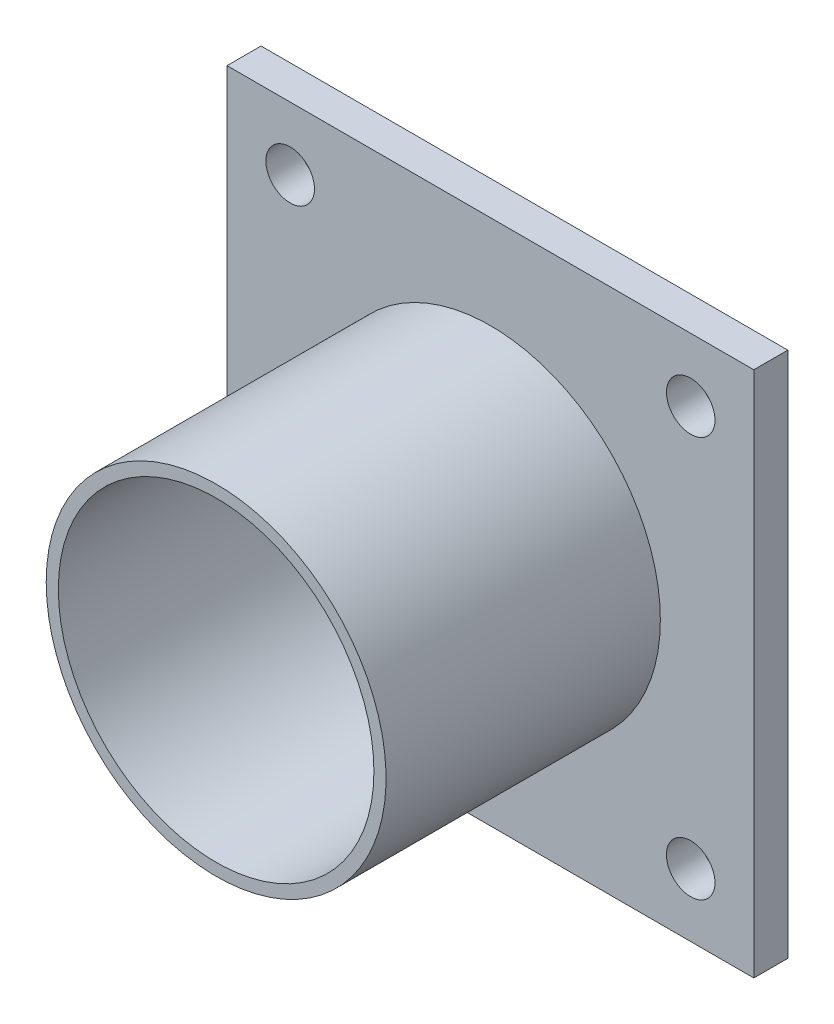
SolidWorks part; units mm, degrees
material "Алюминиевая бронза"
ref_plane "Спереди" through (0, 0, 0) normal (0, 0, 1) x (1, 0, 0)
ref_plane "Сверху" through (0, 0, 0) normal (0, 1, 0) x (1, 0, 0)
ref_plane "Справа" through (0, 0, 0) normal (1, 0, 0) x (0, 0, -1)
sketch "Эскиз1" plane through (0, 0, 0) normal (0, 0, 1) x (1, 0, 0)
  line L0 (0, 10.85) -> (21.7, 10.85) construction
  line L1 (0, 0) -> (21.7, 0)
  line L2 (0, 0) -> (0, 21.7)
  line L3 (0, 21.7) -> (21.7, 21.7)
  line L4 (21.7, 0) -> (21.7, 21.7)
  line L5 (10.85, 21.7) -> (10.85, 0) construction
  circle A0 centre (2.6, 19.1) radius 1
  circle A1 centre (10.85, 10.85) radius 7
  circle A2 centre (19.1, 19.1) radius 1
  circle A3 centre (19.1, 2.6) radius 1
  circle A4 centre (2.6, 2.6) radius 1
  dimension "D3" = 2.6
  dimension "D5" = 2
  dimension "D1" = 21.7
  dimension "D2" = 21.7
  dimension "D4" = 2.6
  dimension "D6" = 2
extrude "Бобышка-Вытянуть1" add sketch "Эскиз1" along normal blind 1.4
sketch "Эскиз2" plane through (0, 0, 0) normal (0, 0, -1) x (-1, 0, 0)
  circle A0 centre (-10.85, 10.85) radius 7
extrude "Вытянуть-Тонкостенный1" add sketch "Эскиз2" against normal blind 12.7 thin thin type one direction reverse wall 0.5
